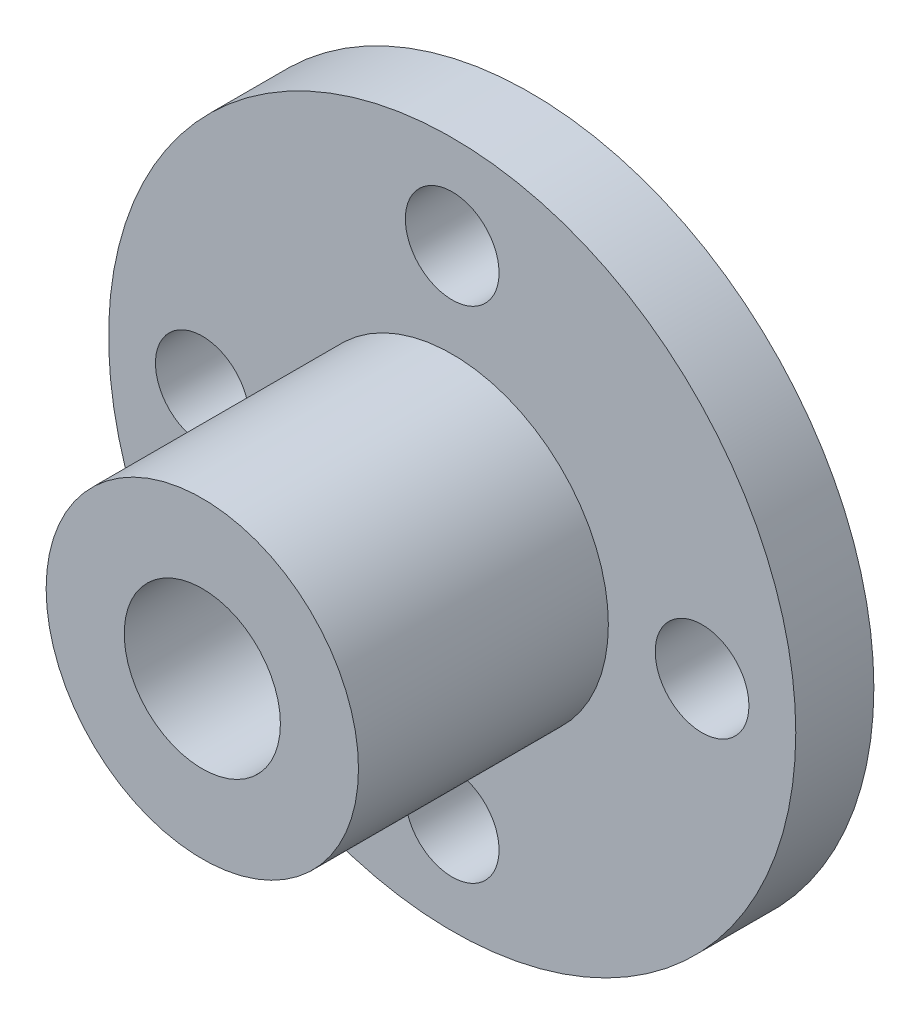
SolidWorks part; units mm, degrees
ref_plane "前视基准面" through (0, 0, 0) normal (0, 0, 1) x (1, 0, 0)
ref_plane "上视基准面" through (0, 0, 0) normal (0, 1, 0) x (1, 0, 0)
ref_plane "右视基准面" through (0, 0, 0) normal (1, 0, 0) x (0, 0, -1)
other "Configuration Table"
sketch "草图1" plane through (0, 0, 0) normal (0, 0, 1) x (1, 0, 0)
  circle A0 centre (0, 0) radius 11
  dimension "D1" = 22
extrude "凸台-拉伸1" add sketch "草图1" along normal blind 2.5
sketch "草图2" plane through (0, 0, 2.5) normal (0, 0, 1) x (1, 0, 0)
  circle A0 centre (0, 0) radius 5
  dimension "D1" = 10
extrude "凸台-拉伸2" add sketch "草图2" along normal blind 8
sketch "草图3" plane through (0, 0, 10.5) normal (0, 0, 1) x (1, 0, 0)
  circle A0 centre (0, 0) radius 2.5
  dimension "D1" = 5
extrude "切除-拉伸1" cut sketch "草图3" against normal up to next
sketch "草图4" plane through (0, 0, 2.5) normal (0, 0, 1) x (1, 0, 0)
  circle A0 centre (0, 0) radius 8 construction
  circle A1 centre (8, 0) radius 1.5
  circle A2 centre (0, -8) radius 1.5
  circle A3 centre (0, 0) radius 8 construction
  circle A4 centre (-8, 0) radius 1.5
  circle A5 centre (0, 0) radius 8 construction
  circle A6 centre (0, 8) radius 1.5
  circle A7 centre (0, 0) radius 8 construction
  point P17 (0, 0)
  dimension "D1" = 16
  dimension "D2" = 3
  dimension "D3" = 4
extrude "切除-拉伸2" cut sketch "草图4" against normal up to next
